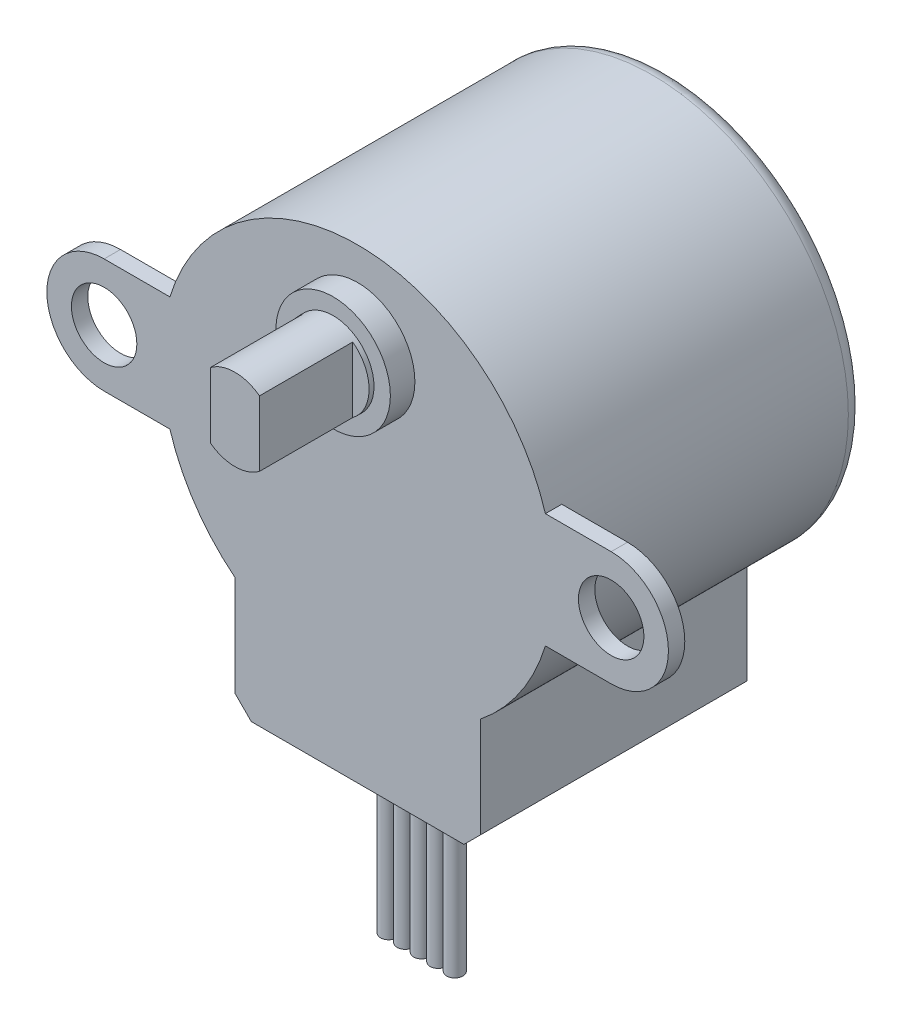
SolidWorks part; units mm, degrees
material "Сталь 3 ГОСТ 535-88"
ref_plane "Спереди" through (0, 0, 0) normal (0, 0, 1) x (1, 0, 0)
ref_plane "Сверху" through (0, 0, 0) normal (0, 1, 0) x (1, 0, 0)
ref_plane "Сбоку" through (0, 0, 0) normal (1, 0, 0) x (0, 0, -1)
sketch "Эскиз1" plane through (0, 0, 0) normal (0, 0, 1) x (1, 0, 0)
  circle A0 centre (0, 0) radius 12
  dimension "D1" = 24
extrude "Бобышка-Вытянуть1" add sketch "Эскиз1" along normal blind 19
sketch "Эскиз2" plane through (0, 0, 19) normal (0, 0, 1) x (1, 0, 0)
  line L0 (0, 12) -> (0, -12) construction
  line L1 (-15.5, 0) -> (0, 0) construction
  line L2 (-15.5, 3.5) -> (-11.4782, 3.5)
  line L3 (-15.5, -3.5) -> (-11.4782, -3.5)
  line L4 (15.5, -3.5) -> (11.4782, -3.5)
  line L5 (15.5, 3.5) -> (11.4782, 3.5)
  circle A0 centre (0, 0) radius 12 construction
  circle A1 centre (-15.5, 0) radius 2
  arc A2 (-15.5, 3.5) -> (-15.5, -3.5) centre (-15.5, 0) ccw
  arc A3 (-11.4782, 3.5) -> (-11.4782, -3.5) centre (0, 0) ccw
  arc A4 (11.4782, 3.5) -> (11.4782, -3.5) centre (0, 0) cw
  arc A5 (15.5, 3.5) -> (15.5, -3.5) centre (15.5, 0) cw
  circle A6 centre (15.5, 0) radius 2
  dimension "D1" = 4
  dimension "D3" = 7
  dimension "D2" = 15.5
extrude "Бобышка-Вытянуть2" add sketch "Эскиз2" against normal blind 1
sketch "Эскиз3" plane through (0, 0, 19) normal (0, 0, 1) x (1, 0, 0)
  circle A0 centre (0, 6.5) radius 3.5
  dimension "D2" = 7
  dimension "D1" = 6.5
extrude "Бобышка-Вытянуть3" add sketch "Эскиз3" along normal blind 1.5
sketch "Эскиз4" plane through (0, 0, 20.5) normal (0, 0, 1) x (1, 0, 0)
  line L1 (0, 9) -> (0, 4) construction
  circle A0 centre (0, 6.5) radius 2.5
  dimension "D1" = 5
extrude "Бобышка-Вытянуть4" add sketch "Эскиз4" along normal blind 6
sketch "Эскиз5" plane through (0, 0, 26.5) normal (0, 0, 1) x (1, 0, 0)
  line L0 (-1.5, 8.5) -> (-1.5, 4.5)
  line L1 (0, 9) -> (0, 4) construction
  line L2 (1.5, 8.5) -> (1.5, 4.5)
  circle A0 centre (0, 6.5) radius 2.5 construction
  circle A1 centre (0, 6.5) radius 2.5 construction
  arc A2 (-1.5, 8.5) -> (-1.5, 4.5) centre (0, 6.5) ccw
  arc A3 (1.5, 8.5) -> (1.5, 4.5) centre (0, 6.5) cw
  dimension "D1" = 3
extrude "Вырез-Вытянуть1" cut sketch "Эскиз5" against normal blind 5.7
sketch "Эскиз6" plane through (0, 0, 19) normal (0, 0, 1) x (1, 0, 0)
  line L0 (-7.5, -16.5) -> (7.5, -16.5)
  line L1 (0, 0) -> (0, -16.5) construction
  line L2 (-7.5, -16.5) -> (-7.5, -9.3675)
  line L3 (7.5, -16.5) -> (7.5, -9.3675)
  arc A0 (-11.4782, -3.5) -> (11.4782, -3.5) centre (0, 0) ccw construction
  arc A1 (-7.5, -9.3675) -> (7.5, -9.3675) centre (0, 0) ccw
  dimension "D1" = 16.5
  dimension "D2" = 15
extrude "Бобышка-Вытянуть5" add sketch "Эскиз6" against normal blind 16.3
chamfer "Фаска1" distance 1 angle 45 2 edges at (7.5, -16.5, 10.85) (-7.5, -16.5, 10.85)
fillet "Скругление1" radius 1 1 edges at (12, 0, 0)
sketch "Эскиз7" plane through (0, -16.5, 0) normal (0, -1, 0) x (1, 0, 0)
  line L0 (-3.5, 15) -> (3.5, 15) construction
  line L1 (-3.5, 15.6) -> (3.5, 15.6)
  line L2 (-3.5, 14.4) -> (3.5, 14.4)
  line L3 (0, 19) -> (0, 2.7) construction
  line L4 (-6.5, 19) -> (6.5, 19) construction
  line L5 (-6.5, 2.7) -> (6.5, 2.7) construction
  arc A0 (-3.5, 15.6) -> (-3.5, 14.4) centre (-3.5, 15) ccw
  arc A1 (3.5, 14.4) -> (3.5, 15.6) centre (3.5, 15) ccw
  point P2 (0, 15)
  dimension "D1" = 1.2
  dimension "D2" = 7
  dimension "D3" = 4
extrude "Вырез-Вытянуть2" cut sketch "Эскиз7" against normal blind 2
sketch "Эскиз8" plane through (0, -14.5, 0) normal (0, -1, 0) x (1, 0, 0)
  line L0 (-4.1, 15) -> (4.1, 15) construction
  arc A0 (-3.5, 15.6) -> (-3.5, 14.4) centre (-3.5, 15) ccw construction
  arc A1 (3.5, 14.4) -> (3.5, 15.6) centre (3.5, 15) ccw construction
  circle A2 centre (-2.1, 15) radius 0.5
  circle A3 centre (-1.09, 15) radius 0.5
  circle A4 centre (-0.08, 15) radius 0.5
  circle A5 centre (0.93, 15) radius 0.5
  circle A6 centre (1.94, 15) radius 0.5
  dimension "D1" = 1
  dimension "D3" = 2
  dimension "D2" = 5
extrude "Бобышка-Вытянуть6" add sketch "Эскиз8" along normal blind 13
